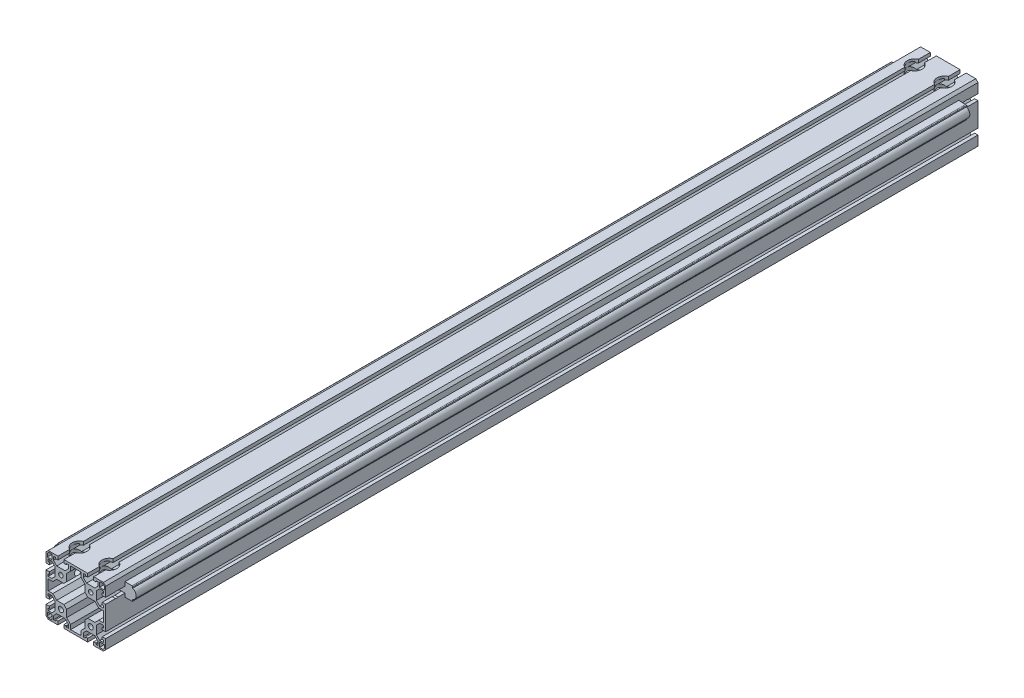
SolidWorks part; units mm, degrees
material "6061 Aluminum Alloy"
ref_plane "Front Plane" through (0, 0, 0) normal (0, 0, 1) x (1, 0, 0)
ref_plane "Top Plane" through (0, 0, 0) normal (0, 1, 0) x (1, 0, 0)
ref_plane "Right Plane" through (0, 0, 0) normal (1, 0, 0) x (0, 0, -1)
sketch "Sketch1" plane through (0, 0, 0) normal (0, 0, 1) x (1, 0, 0)
  line L0 (6, 3) -> (3, 3)
  line L1 (3, 3) -> (3, 4.5)
  line L2 (3, 4.5) -> (0, 4.5)
  line L3 (0, 4.5) -> (0, 0)
  line L4 (0, 0) -> (32, 0)
  line L5 (32, 0) -> (32, 4.5)
  line L6 (32, 4.5) -> (29, 4.5)
  line L7 (29, 4.5) -> (29, 3)
  line L8 (29, 3) -> (26, 3)
  line L9 (26, 3) -> (26, 7.875)
  line L10 (26, 7.875) -> (30.375, 12.25)
  line L11 (30.375, 12.25) -> (41.625, 12.25)
  line L12 (41.625, 12.25) -> (46, 7.875)
  line L13 (46, 7.875) -> (46, 3)
  line L14 (46, 3) -> (43, 3)
  line L15 (43, 3) -> (43, 4.5)
  line L16 (43, 4.5) -> (40, 4.5)
  line L17 (40, 4.5) -> (40, 0)
  line L18 (40, 0) -> (53, 0)
  line L19 (53, 0) -> (56, 3)
  line L20 (56, 3) -> (56, 16)
  line L21 (56, 16) -> (51.5, 16)
  line L22 (51.5, 16) -> (51.5, 13)
  line L23 (51.5, 13) -> (53, 13)
  line L24 (53, 13) -> (53, 10)
  line L25 (53, 10) -> (48.125, 10)
  line L26 (48.125, 10) -> (43.75, 14.375)
  line L27 (43.75, 14.375) -> (43.75, 25.625)
  line L28 (43.75, 25.625) -> (48.125, 30)
  line L29 (48.125, 30) -> (53, 30)
  line L30 (53, 30) -> (53, 27)
  line L31 (53, 27) -> (51.5, 27)
  line L32 (51.5, 27) -> (51.5, 24)
  line L33 (51.5, 24) -> (56, 24)
  line L34 (56, 24) -> (56, 56)
  line L35 (56, 56) -> (51.5, 56)
  line L36 (51.5, 56) -> (51.5, 53)
  line L37 (51.5, 53) -> (53, 53)
  line L38 (53, 53) -> (53, 50)
  line L39 (53, 50) -> (48.125, 50)
  line L40 (48.125, 50) -> (43.75, 54.375)
  line L41 (43.75, 54.375) -> (43.75, 65.625)
  line L42 (43.75, 65.625) -> (48.125, 70)
  line L43 (48.125, 70) -> (53, 70)
  line L44 (53, 70) -> (53, 67)
  line L45 (53, 67) -> (51.5, 67)
  line L46 (51.5, 67) -> (51.5, 64)
  line L47 (51.5, 64) -> (56, 64)
  line L48 (56, 64) -> (56, 77)
  line L49 (56, 77) -> (53, 80)
  line L50 (53, 80) -> (40, 80)
  line L51 (40, 80) -> (40, 75.5)
  line L52 (40, 75.5) -> (43, 75.5)
  line L53 (43, 75.5) -> (43, 77)
  line L54 (43, 77) -> (46, 77)
  line L55 (46, 77) -> (46, 72.125)
  line L56 (46, 72.125) -> (41.625, 67.75)
  line L57 (41.625, 67.75) -> (30.375, 67.75)
  line L58 (30.375, 67.75) -> (26, 72.125)
  line L59 (26, 72.125) -> (26, 77)
  line L60 (26, 77) -> (29, 77)
  line L61 (29, 77) -> (29, 75.5)
  line L62 (29, 75.5) -> (32, 75.5)
  line L63 (32, 75.5) -> (32, 80)
  line L64 (32, 80) -> (0, 80)
  line L65 (0, 80) -> (0, 75.5)
  line L66 (0, 75.5) -> (3, 75.5)
  line L67 (3, 75.5) -> (3, 77)
  line L68 (3, 77) -> (6, 77)
  line L69 (6, 77) -> (6, 72.125)
  line L70 (6, 72.125) -> (1.625, 67.75)
  line L71 (1.625, 67.75) -> (-9.625, 67.75)
  line L72 (-9.625, 67.75) -> (-14, 72.125)
  line L73 (-14, 72.125) -> (-14, 77)
  line L74 (-14, 77) -> (-11, 77)
  line L75 (-11, 77) -> (-11, 75.5)
  line L76 (-11, 75.5) -> (-8, 75.5)
  line L77 (-8, 75.5) -> (-8, 80)
  line L78 (-8, 80) -> (-21, 80)
  line L79 (-21, 80) -> (-24, 77)
  line L80 (-24, 77) -> (-24, 64)
  line L81 (-24, 64) -> (-19.5, 64)
  line L82 (-19.5, 64) -> (-19.5, 67)
  line L83 (-19.5, 67) -> (-21, 67)
  line L84 (-21, 67) -> (-21, 70)
  line L85 (-21, 70) -> (-16.125, 70)
  line L86 (-16.125, 70) -> (-11.75, 65.625)
  line L87 (-11.75, 65.625) -> (-11.75, 54.375)
  line L88 (-11.75, 54.375) -> (-16.125, 50)
  line L89 (-16.125, 50) -> (-21, 50)
  line L90 (-21, 50) -> (-21, 53)
  line L91 (-21, 53) -> (-19.5, 53)
  line L92 (-19.5, 53) -> (-19.5, 56)
  line L93 (-19.5, 56) -> (-24, 56)
  line L94 (-24, 56) -> (-24, 24)
  line L95 (-24, 24) -> (-19.5, 24)
  line L96 (-19.5, 24) -> (-19.5, 27)
  line L97 (-19.5, 27) -> (-21, 27)
  line L98 (-21, 27) -> (-21, 30)
  line L99 (-21, 30) -> (-16.125, 30)
  line L100 (-16.125, 30) -> (-11.75, 25.625)
  line L101 (-11.75, 25.625) -> (-11.75, 14.375)
  line L102 (-11.75, 14.375) -> (-16.125, 10)
  line L103 (-16.125, 10) -> (-21, 10)
  line L104 (-21, 10) -> (-21, 13)
  line L105 (-21, 13) -> (-19.5, 13)
  line L106 (-19.5, 13) -> (-19.5, 16)
  line L107 (-19.5, 16) -> (-24, 16)
  line L108 (-24, 16) -> (-24, 3)
  line L109 (-24, 3) -> (-21, 0)
  line L110 (-21, 0) -> (-8, 0)
  line L111 (-8, 0) -> (-8, 4.5)
  line L112 (-8, 4.5) -> (-11, 4.5)
  line L113 (-11, 4.5) -> (-11, 3)
  line L114 (-11, 3) -> (-14, 3)
  line L115 (-14, 3) -> (-14, 7.875)
  line L116 (-14, 7.875) -> (-9.625, 12.25)
  line L117 (-9.625, 12.25) -> (1.625, 12.25)
  line L118 (1.625, 12.25) -> (6, 7.875)
  line L119 (6, 7.875) -> (6, 3)
  line L120 (47.78, 1.78) -> (47.78, 8.22)
  line L121 (47.78, 8.22) -> (54.22, 8.22)
  line L122 (54.22, 8.22) -> (54.22, 3.7373)
  line L123 (54.22, 3.7373) -> (52.2627, 1.78)
  line L124 (52.2627, 1.78) -> (47.78, 1.78)
  line L125 (-15.78, 8.22) -> (-15.78, 1.78)
  line L126 (-15.78, 1.78) -> (-20.2627, 1.78)
  line L127 (-20.2627, 1.78) -> (-22.22, 3.7373)
  line L128 (-22.22, 3.7373) -> (-22.22, 8.22)
  line L129 (-22.22, 8.22) -> (-15.78, 8.22)
  line L130 (47.78, 71.78) -> (47.78, 78.22)
  line L131 (47.78, 78.22) -> (52.2627, 78.22)
  line L132 (52.2627, 78.22) -> (54.22, 76.2627)
  line L133 (54.22, 76.2627) -> (54.22, 71.78)
  line L134 (54.22, 71.78) -> (47.78, 71.78)
  line L135 (-15.78, 78.22) -> (-15.78, 71.78)
  line L136 (-15.78, 71.78) -> (-22.22, 71.78)
  line L137 (-22.22, 71.78) -> (-22.22, 76.2627)
  line L138 (-22.22, 76.2627) -> (-20.2627, 78.22)
  line L139 (-20.2627, 78.22) -> (-15.78, 78.22)
  line L140 (41.6324, 27.75) -> (32.0343, 27.75)
  line L141 (32.0343, 27.75) -> (28.25, 23.9657)
  line L142 (28.25, 23.9657) -> (28.25, 14.3676)
  line L143 (28.25, 14.3676) -> (23, 9.1176)
  line L144 (23, 9.1176) -> (23, 3)
  line L145 (23, 3) -> (9, 3)
  line L146 (9, 3) -> (9, 9.1176)
  line L147 (9, 9.1176) -> (3.75, 14.3676)
  line L148 (3.75, 14.3676) -> (3.75, 23.9657)
  line L149 (3.75, 23.9657) -> (-0.0343, 27.75)
  line L150 (-0.0343, 27.75) -> (-9.6324, 27.75)
  line L151 (-9.6324, 27.75) -> (-14.8824, 33)
  line L152 (-14.8824, 33) -> (-21, 33)
  line L153 (-21, 33) -> (-21, 47)
  line L154 (-21, 47) -> (-14.8824, 47)
  line L155 (-14.8824, 47) -> (-9.6324, 52.25)
  line L156 (-9.6324, 52.25) -> (-0.0343, 52.25)
  line L157 (-0.0343, 52.25) -> (3.75, 56.0343)
  line L158 (3.75, 56.0343) -> (3.75, 65.6324)
  line L159 (3.75, 65.6324) -> (9, 70.8824)
  line L160 (9, 70.8824) -> (9, 77)
  line L161 (9, 77) -> (23, 77)
  line L162 (23, 77) -> (23, 70.8824)
  line L163 (23, 70.8824) -> (28.25, 65.6324)
  line L164 (28.25, 65.6324) -> (28.25, 56.0343)
  line L165 (28.25, 56.0343) -> (32.0343, 52.25)
  line L166 (32.0343, 52.25) -> (41.6324, 52.25)
  line L167 (41.6324, 52.25) -> (46.8824, 47)
  line L168 (46.8824, 47) -> (53, 47)
  line L169 (53, 47) -> (53, 33)
  line L170 (53, 33) -> (46.8824, 33)
  line L171 (46.8824, 33) -> (41.6324, 27.75)
  circle A0 centre (36, 20) radius 3
  circle A1 centre (36, 60) radius 3
  circle A2 centre (-4, 20) radius 3
  circle A3 centre (-4, 60) radius 3
extrude "BEAM LENGTH" add sketch "Sketch1" along normal up to vertex (585.5 mm away) and the other way up to vertex (585.5 mm away) contours L118 L119 L0 L1 L2 L3 L4 L5 L6 L7 L8 L9 L10 L11 L12 L13 L14 L15 L16 L17 L18 L19 L20 L21 L22 L23 L24 L25 L26 L27 L28 L29 L30 L31 L32 L33 L34 L35 L36 L37 L38 L39 L40 L41 L42 L43 L44 L45 L46 L47 L48
hole_wizard "M8x1.25 Tapped Hole4" positions "Sketch17" profile "Sketch16" tap size "M8x1.25" standard "Ansi Metric"
sketch "Sketch17" plane through (0, 0, 585.5) normal (0, 0, 1) x (1, 0, 0)
  point P0 (-4, 20)
  point P1 (36, 20)
sketch "Sketch16" plane through (-4, 20, 585.5) normal (1, 0, 0) x (0, -1, 0)
  line L0 (0, 0) -> (0, 21.0929)
  line L1 (0, 21.0929) -> (3.4, 19.05)
  line L2 (3.4, 19.05) -> (3.4, 0)
  line L5 (3.4, 0) -> (0, 0)
  line L10 (0, 21.0929) -> (-3.4, 19.05) construction
  line L11 (0, -6.35) -> (0, 107.95) construction
  dimension "Tap Drill Dia." = 6.8
  dimension "Tap Drill Depth" = 19.05
  dimension "Drill Angle" = 118
cosmetic thread "Hole Thread9" parameters "D1"=19.05, "D2"=8
cosmetic thread "Hole Thread10" parameters "D1"=19.05, "D2"=8
hole_wizard "M8x1.25 Tapped Hole5" positions "Sketch19" profile "Sketch18" tap size "M8x1.25" standard "Ansi Metric"
sketch "Sketch19" plane through (0, 0, -585.5) normal (0, 0, -1) x (-1, 0, 0)
  point P0 (4, 20)
  point P1 (-36, 20)
sketch "Sketch18" plane through (-4, 20, -585.5) normal (1, 0, 0) x (0, 1, 0)
  line L0 (0, 0) -> (0, 21.0929)
  line L1 (0, 21.0929) -> (3.4, 19.05)
  line L2 (3.4, 19.05) -> (3.4, 0)
  line L5 (3.4, 0) -> (0, 0)
  line L10 (0, 21.0929) -> (-3.4, 19.05) construction
  line L11 (0, -6.35) -> (0, 107.95) construction
  dimension "Tap Drill Dia." = 6.8
  dimension "Tap Drill Depth" = 19.05
  dimension "Drill Angle" = 118
cosmetic thread "Hole Thread11" parameters "D1"=19.05, "D2"=8
cosmetic thread "Hole Thread12" parameters "D1"=19.05, "D2"=8
hole_wizard "11/32 (0.34375) Diameter Hole2" positions "Sketch29" profile "Sketch28" hole size "11/32" standard "Ansi Inch" end condition through all
sketch "Sketch29" plane through (56, 0, 0) normal (1, 0, 0) x (0, 0, -1)
  line L0 (-585.5, 80) -> (585.5, 80) construction
  line L1 (-585.5, 64) -> (-585.5, 77) construction
  line L2 (585.5, 24) -> (585.5, 56) construction
  point P0 (-570.5, 60)
  point P1 (570.5, 60)
  dimension "D1" = 20
  dimension "D2" = 15
  dimension "D3" = 15
sketch "Sketch28" plane through (56, 60, 570.5) normal (0, 1, 0) x (0, 0, -1)
  line L0 (0, 0) -> (0, 80)
  line L1 (0, 80) -> (4.3656, 80)
  line L2 (4.3656, 80) -> (4.3656, 0)
  line L5 (4.3656, 0) -> (0, 0)
  line L11 (0, -6.35) -> (0, 107.95) construction
  dimension "Thru Hole Dia." = 8.7312
  dimension "Thru Hole Depth" = 80
hole_wizard "Ø20.0 (20) Diameter Hole1" positions "Sketch32" profile "Sketch31" hole size "Ø20.0" standard "ANSI Metric"
sketch "Sketch32" plane through (0, 80, 0) normal (0, 1, 0) x (1, 0, 0)
  line L0 (-8, 585.5) -> (-21, 585.5) construction
  line L1 (-24, -585.5) -> (-24, 585.5) construction
  line L2 (56, -585.5) -> (56, 585.5) construction
  line L3 (32, -585.5) -> (0, -585.5) construction
  point P0 (-4, 560.5)
  point P2 (36, 560.5)
  point P4 (-4, -560.5)
  point P6 (36, -560.5)
  dimension "D1" = 25
  dimension "D2" = 20
  dimension "D3" = 20
  dimension "D4" = 25
sketch "Sketch31" plane through (-4, 80, -560.5) normal (1, 0, 0) x (0, 0, 1)
  line L0 (0, 0) -> (0, 16)
  line L1 (0, 16) -> (10, 16)
  line L2 (10, 16) -> (10, 0)
  line L5 (10, 0) -> (0, 0)
  line L10 (0, 16) -> (-10, 16) construction
  line L11 (0, -6.35) -> (0, 107.95) construction
  dimension "Hole Dia." = 20
  dimension "Hole Depth" = 16
  dimension "Drill Angle" = 180
sketch "Sketch34" plane through (0, 0, 0) normal (0, 0, 1) x (1, 0, 0)
  line L0 (-34.4, 66.8257) -> (-34.4, 68.25)
  line L1 (-33.4, 69.25) -> (-24, 69.25)
  line L2 (-24, 69.25) -> (-24, 64)
  line L3 (-24, 77) -> (-24, 64) construction
  line L5 (-24, 64) -> (-12.4, 64)
  line L6 (-12.4, 64) -> (-12.4, 56)
  line L7 (-34.4, 53.6743) -> (-34.4, 52.25)
  line L8 (-33.4, 51.25) -> (-24, 51.25)
  line L9 (-24, 56) -> (-24, 24) construction
  line L10 (-24, 51.25) -> (-24, 56)
  line L11 (-24, 56) -> (-12.4, 56)
  line L12 (66.4, 66.8257) -> (66.4, 68.25)
  line L13 (65.4, 69.25) -> (56, 69.25)
  line L14 (56, 69.25) -> (56, 64)
  line L15 (56, 64) -> (44.4, 64)
  line L16 (44.4, 64) -> (44.4, 56)
  line L17 (66.4, 53.6743) -> (66.4, 52.25)
  line L18 (65.4, 51.25) -> (56, 51.25)
  line L19 (56, 51.25) -> (56, 56)
  line L20 (56, 24) -> (56, 56) construction
  line L21 (56, 56) -> (44.4, 56)
  circle A0 centre (-32, 60.25) radius 7
  circle A1 centre (64, 60.25) radius 7
  arc A2 (-33.4, 51.25) -> (-34.4, 52.25) centre (-33.4, 52.25) cw
  arc A3 (-34.4, 68.25) -> (-33.4, 69.25) centre (-33.4, 68.25) cw
  arc A4 (65.4, 51.25) -> (66.4, 52.25) centre (65.4, 52.25) ccw
  arc A5 (66.4, 68.25) -> (65.4, 69.25) centre (65.4, 68.25) ccw
  dimension "D1" = 14
  dimension "D2" = 14
  dimension "D3" = 8
extrude "Boss-Extrude1" add sketch "Sketch34" along normal offset from surface 26 and the other way offset from surface (559.5 mm away) 26 contours A0 | A3 L0 A0 L7 A2 L8 L10 L11 L6 L5 L2 L1 | L12 A5 L13 L14 L15 L16 L21 L19 L18 A4 L17 A1 | A1 up to face at (-0.6, 20, 585.5) other way up to face at (-7.4, 20, -585.5)
